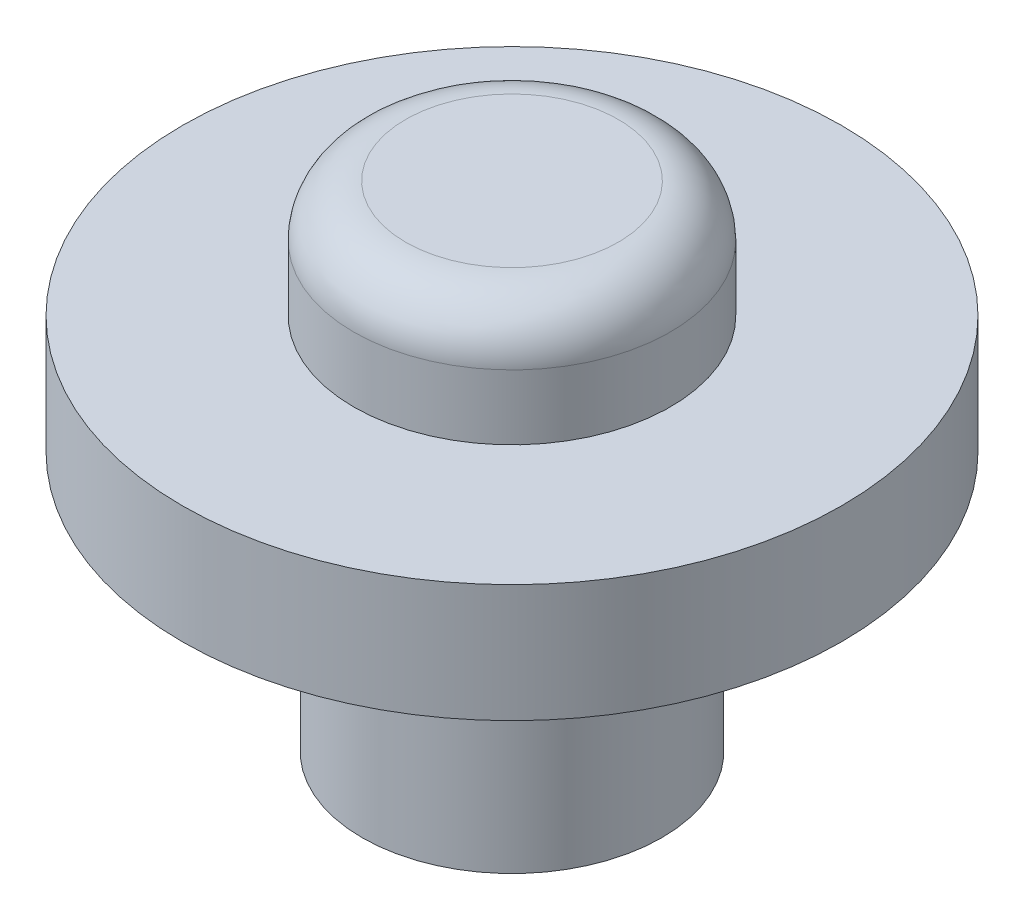
SolidWorks part; units mm, degrees
ref_plane "Front" through (0, 0, 0) normal (0, 0, 1) x (1, 0, 0)
ref_plane "Top" through (0, 0, 0) normal (0, 1, 0) x (1, 0, 0)
ref_plane "Right" through (0, 0, 0) normal (1, 0, 0) x (0, 0, -1)
sketch "Sketch1" plane through (0, 0, 0) normal (0, 1, 0) x (1, 0, 0)
  circle A0 centre (0, 0) radius 5.775
  dimension "D1" = 11.55
extrude "Boss-Extrude1" add sketch "Sketch1" against normal blind 10
sketch "Sketch2" plane through (0, 0, 0) normal (0, 1, 0) x (1, 0, 0)
  circle A0 centre (0, 0) radius 12.7
  dimension "D1" = 25.4
extrude "Boss-Extrude2" add sketch "Sketch2" along normal blind 4.54
sketch "Sketch3" plane through (0, 4.54, 0) normal (0, 1, 0) x (1, 0, 0)
  circle A0 centre (0, 0) radius 6.1
  dimension "D1" = 12.2
extrude "Boss-Extrude3" add sketch "Sketch3" along normal blind 4.5 contours A0
fillet "Fillet1" radius 2 1 edges at (0, 9.04, 6.1)
